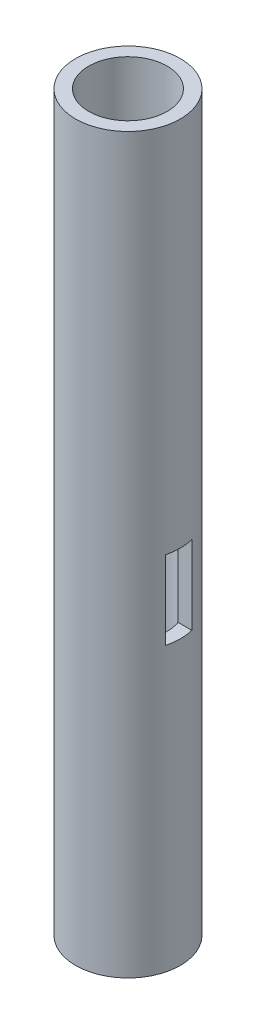
SolidWorks part; units mm, degrees
material "Delrin 2700 NC010, Low Viscosity Acetal Copolymer (SS)"
ref_plane "Front Plane" through (0, 0, 0) normal (0, 0, 1) x (1, 0, 0)
ref_plane "Top Plane" through (0, 0, 0) normal (0, 1, 0) x (1, 0, 0)
ref_plane "Right Plane" through (0, 0, 0) normal (1, 0, 0) x (0, 0, -1)
sketch "Sketch1" plane through (0, 0, 0) normal (0, 1, 0) x (1, 0, 0)
  circle A0 centre (0, 0) radius 9.525
  circle A1 centre (0, 0) radius 12.7
  dimension "D1" = 25.4
  dimension "D2" = 19.05
extrude "Boss-Extrude1" add sketch "Sketch1" along normal blind 177.8
sketch "Sketch2" plane through (0, 0, 0) normal (1, 0, 0) x (0, 0, -1)
  line L0 (-3.175, 75.8083) -> (0, 75.8083) construction
  line L1 (-3.175, 68.6206) -> (3.175, 68.6206)
  line L2 (-3.175, 68.6206) -> (-3.175, 87.6706)
  line L3 (-3.175, 87.6706) -> (3.175, 87.6706)
  line L4 (3.175, 68.6206) -> (3.175, 87.6706)
  line L5 (0, 13.97) -> (0, -13.97) construction
  line L6 (0, 75.8083) -> (3.175, 75.8083) construction
  line L7 (13.97, 0) -> (-13.97, 0) construction
  dimension "D1" = 19.05
  dimension "D2" = 87.6706
  dimension "D3" = 6.35
extrude "Cut-Extrude1" cut sketch "Sketch2" against normal through all both and the other way through all
